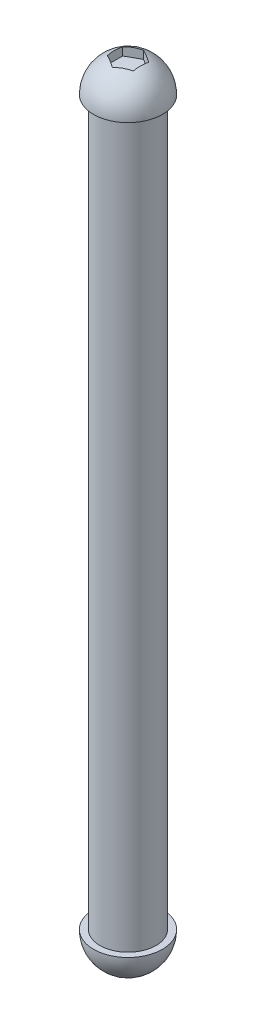
SolidWorks part; units mm, degrees
ref_plane "前视基准面" through (0, 0, 0) normal (0, 0, 1) x (1, 0, 0)
ref_plane "上视基准面" through (0, 0, 0) normal (0, 1, 0) x (1, 0, 0)
ref_plane "右视基准面" through (0, 0, 0) normal (1, 0, 0) x (0, 0, -1)
other "Configuration Table"
sketch "草图1" plane through (0, 0, 0) normal (0, 1, 0) x (1, 0, 0)
  line L0 (0.2272, 2.9914) -> (-0.2272, -2.9914) construction
  circle A0 centre (0, 0) radius 3
revolve "旋转1" add sketch "草图1" angle 180 about L0
ref_plane "基准面1" through (0, -3, 0) normal (0, -1, 0) x (-1, 0, 0)
sketch "草图2" plane through (0, -3, 0) normal (0, -1, 0) x (-1, 0, 0)
  line L1 (1.1614, -0.6466) -> (1.1406, 0.6825)
  line L2 (1.1406, 0.6825) -> (-0.0207, 1.3291)
  line L3 (-0.0207, 1.3291) -> (-1.1614, 0.6466)
  line L4 (-1.1614, 0.6466) -> (-1.1406, -0.6825)
  line L5 (-1.1406, -0.6825) -> (0.0207, -1.3291)
  line L6 (0.0207, -1.3291) -> (1.1614, -0.6466)
  circle A0 centre (0, 0) radius 1.1511 construction
extrude "切除-拉伸1" cut sketch "草图2" against normal blind 1
sketch "草图3" plane through (0, 0, 0) normal (0, 1, 0) x (1, 0, 0)
  circle A0 centre (0, 0) radius 2.44
extrude "凸台-拉伸1" add sketch "草图3" along normal blind 31.5
mirror "镜向1" about plane through (0, 31.5, 0) normal (0, 1, 0) of bodies 108
